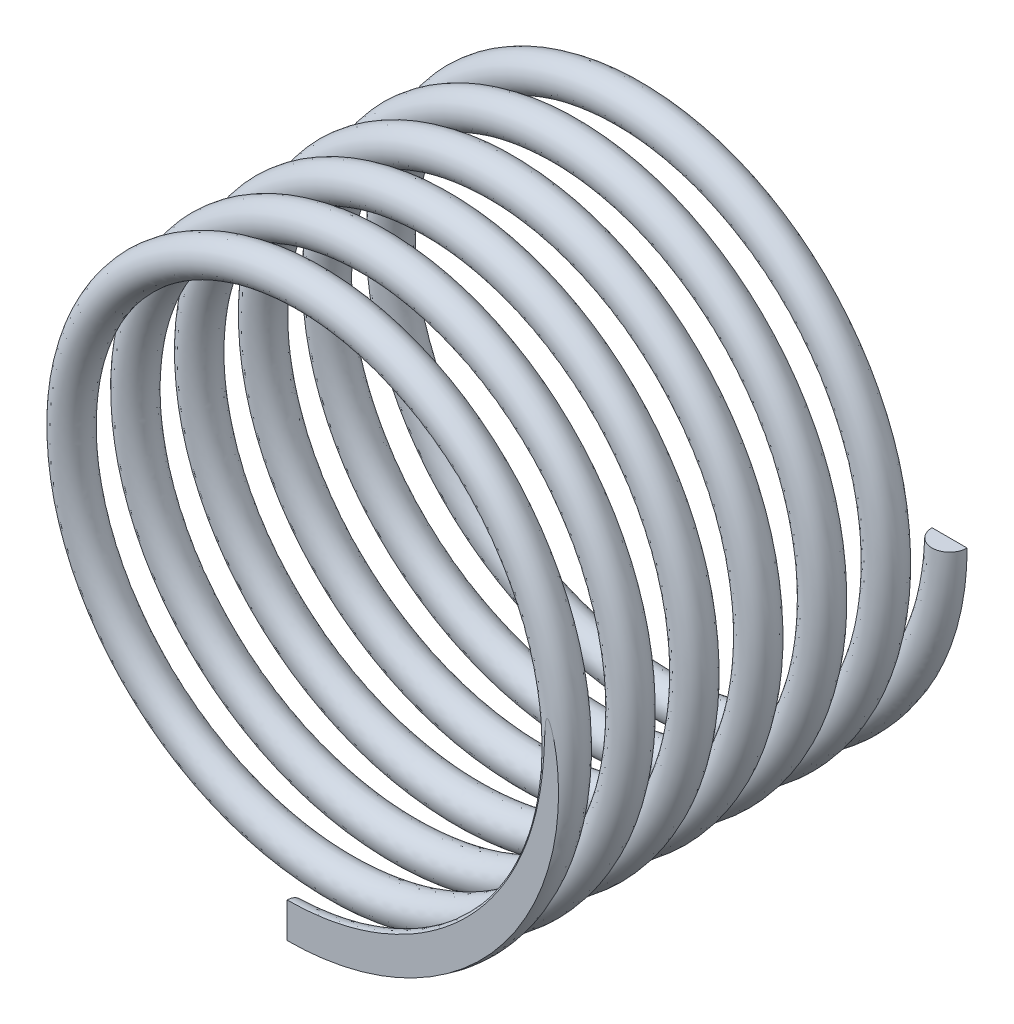
SolidWorks part; units mm, degrees
ref_plane "Front Plane" through (0, 0, 0) normal (0, 0, 1) x (1, 0, 0)
ref_plane "Top Plane" through (0, 0, 0) normal (0, 1, 0) x (1, 0, 0)
ref_plane "Right Plane" through (0, 0, 0) normal (1, 0, 0) x (0, 0, -1)
sketch "Sketch1" plane through (0, 0, 0) normal (0, 0, 1) x (1, 0, 0)
  circle A0 centre (0, 0) radius 16.5
  dimension "D1" = 33
curve "Helix/Spiral1" pitch 4 height 25 turns 6.25
sketch "Sketch2" plane through (0, 0, 0) normal (0, 1, 0) x (1, 0, 0)
  circle A0 centre (16.5, 0) radius 1.1
  spline S0 degree 3 poles (16.5, 0) (16.5, -0.074) (15.8169, -0.2234) (12.8676, -0.4464) (8.3525, -0.6697) (2.8211, -0.8929) (-3.0536, -1.1161) (-8.5568, -1.3393) (-13.0187, -1.5625) (-15.8965, -1.7857) (-16.8399, -2.0089) (-15.7342, -2.2321) (-12.7139, -2.4554) (-8.1466, -2.6786) (-2.5879, -2.9018) (3.2856, -3.125) (8.7594, -3.3482) (13.1673, -3.5714) (15.9729, -3.7946) (16.8349, -4.0179) (15.6484, -4.2411) (12.5578, -4.4643) (7.9391, -4.6875) (2.3543, -4.9107) (-3.517, -5.1339) (-8.9602, -5.3571) (-13.3132, -5.5804) (-16.0462, -5.8036) (-16.8267, -6.0268) (-15.5596, -6.25) (-12.3992, -6.4732) (-7.73, -6.6964) (-2.1202, -6.9196) (3.7476, -7.1429) (9.1594, -7.3661) (13.4566, -7.5893) (16.1164, -7.8125) (16.8151, -8.0357) (15.4677, -8.2589) (12.2381, -8.4821) (7.5194, -8.7054) (1.8857, -8.9286) (-3.9775, -9.1518) (-9.3567, -9.375) (-13.5973, -9.5982) (-16.1833, -9.8214) (-16.8002, -10.0446) (-15.3727, -10.2679) (-12.0746, -10.4911) (-7.3073, -10.7143) (-1.6508, -10.9375) (4.2066, -11.1607) (9.5521, -11.3839) (13.7353, -11.6071) (16.2471, -11.8304) (16.782, -12.0536) (15.2747, -12.2768) (11.9088, -12.5) (7.0938, -12.7232) (1.4155, -12.9464) (-4.4349, -13.1696) (-9.7457, -13.3929) (-13.8706, -13.6161) (-16.3077, -13.8393) (-16.7605, -14.0625) (-15.1737, -14.2857) (-11.7406, -14.5089) (-6.8788, -14.7321) (-1.18, -14.9554) (4.6623, -15.1786) (9.9374, -15.4018) (14.0032, -15.625) (16.3651, -15.8482) (16.7357, -16.0714) (15.0697, -16.2946) (11.5701, -16.5179) (6.6626, -16.7411) (0.9443, -16.9643) (-4.8888, -17.1875) (-10.1271, -17.4107) (-14.1331, -17.6339) (-16.4193, -17.8571) (-16.7076, -18.0804) (-14.9628, -18.3036) (-11.3973, -18.5268) (-6.445, -18.75) (-0.7084, -18.9732) (5.1144, -19.1964) (10.3148, -19.4196) (14.2602, -19.6429) (16.4702, -19.8661) (16.6762, -20.0893) (14.8529, -20.3125) (11.2223, -20.5357) (6.2261, -20.7589) (0.4723, -20.9821) (-5.3389, -21.2054) (-10.5005, -21.4286) (-14.3844, -21.6518) (-16.5179, -21.875) (-16.6415, -22.0982) (-14.7401, -22.3214) (-11.0451, -22.5446) (-6.0061, -22.7679) (-0.2362, -22.9911) (5.5624, -23.2143) (10.6842, -23.4375) (14.5058, -23.6607) (16.5624, -23.8839) (16.6035, -24.1071) (14.6247, -24.3303) (10.8645, -24.5536) (5.7893, -24.7766) (1.9186, -24.926) (0, -25) knots 0 0 0 0 0.008929 0.017857 0.026786 0.035714 0.044643 0.053571 0.0625 0.071429 0.080357 0.089286 0.098214 0.107143 0.116071 0.125 0.133929 0.142857 0.151786 0.160714 0.169643 0.178571 0.1875 0.196429 0.205357 0.214286 0.223214 0.232143 0.241071 0.25 0.258929 0.267857 0.276786 0.285714 0.294643 0.303571 0.3125 0.321429 0.330357 0.339286 0.348214 0.357143 0.366071 0.375 0.383929 0.392857 0.401786 0.410714 0.419643 0.428571 0.4375 0.446429 0.455357 0.464286 0.473214 0.482143 0.491071 0.5 0.508929 0.517857 0.526786 0.535714 0.544643 0.553571 0.5625 0.571429 0.580357 0.589286 0.598214 0.607143 0.616071 0.625 0.633929 0.642857 0.651786 0.660714 0.669643 0.678571 0.6875 0.696429 0.705357 0.714286 0.723214 0.732143 0.741071 0.75 0.758929 0.767857 0.776786 0.785714 0.794643 0.803571 0.8125 0.821429 0.830357 0.839286 0.848214 0.857143 0.866071 0.875 0.883929 0.892857 0.901786 0.910714 0.919643 0.928571 0.9375 0.946429 0.955357 0.964286 0.973214 0.982143 0.991071 1 1 1 1 construction
  dimension "D1" = 2.2
sweep "Sweep1" add profiles "Sketch2" path "Helix/Spiral1"
sketch "Sketch3" plane through (0, 0, 0) normal (0, 1, 0) x (1, 0, 0)
  line L1 (-20.1922, 0) -> (23.7952, 0)
  line L2 (-20.1922, 0) -> (-20.1922, 3.769)
  line L3 (-20.1922, 3.769) -> (23.7952, 3.769)
  line L4 (23.7952, 0) -> (23.7952, 3.769)
  line L5 (-19.8721, -25) -> (22.2149, -25)
  line L6 (-19.8721, -25) -> (-19.8721, -28.072)
  line L7 (-19.8721, -28.072) -> (22.2149, -28.072)
  line L8 (22.2149, -25) -> (22.2149, -28.072)
  dimension "D1" = 25
extrude "Cut-Extrude1" cut sketch "Sketch3" against normal through all and the other way through all
